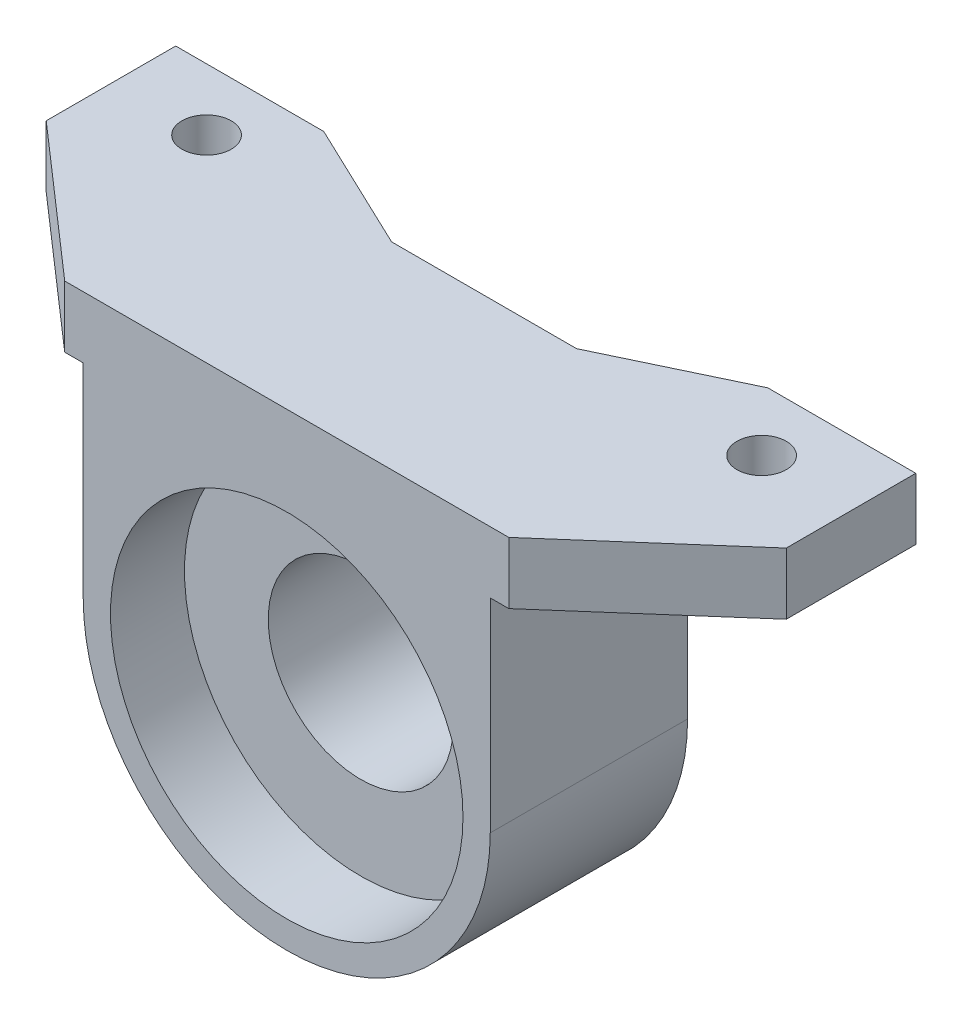
SolidWorks part; units mm, degrees
ref_plane "Plan de face" through (0, 0, 0) normal (0, 0, 1) x (1, 0, 0)
ref_plane "Plan de dessus" through (0, 0, 0) normal (0, 1, 0) x (1, 0, 0)
ref_plane "Plan de droite" through (0, 0, 0) normal (1, 0, 0) x (0, 0, -1)
sketch "Esquisse1" plane through (0, 0, 0) normal (0, 0, 1) x (1, 0, 0)
  circle A0 centre (0, 0) radius 14.29
  circle A1 centre (0, 0) radius 16.5
  dimension "D1" = 28.58
  dimension "D2" = 33
extrude "Boss.-Extru.1" add sketch "Esquisse1" along normal blind 6
sketch "Esquisse2" plane through (0, 0, 0) normal (0, 0, -1) x (-1, 0, 0)
  circle A0 centre (0, 0) radius 16.5
extrude "Boss.-Extru.2" add sketch "Esquisse2" along normal blind 10
ref_plane "Plan2" through (0, 16.5, 0) normal (0, 1, 0) x (1, 0, 0)
sketch "Esquisse3" plane through (0, 16.5, 0) normal (0, 1, 0) x (1, 0, 0)
  line L0 (16.5, 10) -> (-16.5, 10) construction
  line L1 (0, 10) -> (40, 10)
  line L3 (0, -10) -> (40, -10)
  line L4 (40, 10) -> (40, -10)
  line L6 (0, 10) -> (-40, 10)
  line L8 (0, -10) -> (-40, -10)
  line L9 (-40, 10) -> (-40, -10)
  dimension "D1" = 40
  dimension "D2" = 40
  dimension "D3" = 20
extrude "Boss.-Extru.3" add sketch "Esquisse3" along normal blind 5 separate body
ref_plane "Plan3" through (0, 0, -10) normal (0, 0, 1) x (1, 0, 0)
sketch "Esquisse4" plane through (0, 0, -10) normal (0, 0, 1) x (1, 0, 0)
  line L0 (16.5, 16.5) -> (16.5, 0)
  line L1 (8.8, 16.5) -> (-8.8, 16.5) construction
  line L2 (-16.5, 16.5) -> (-16.5, 0)
  line L3 (40, 16.5) -> (-40, 16.5) construction
  line L4 (16.5, 16.5) -> (0, 16.5)
  line L5 (0, 16.5) -> (-16.5, 16.5)
  arc A0 (16.5, 0) -> (0, 16.5) centre (0, 0) ccw
  arc A1 (-16.5, 0) -> (0, 16.5) centre (0, 0) ccw
  circle A2 centre (0, 0) radius 16.5
  dimension "D1" = 16.5
  dimension "D2" = 16.5
  dimension "D3" = 16.5
  dimension "D4" = 16.5
extrude "Boss.-Extru.4" add sketch "Esquisse4" along normal blind 16 contours A2 L5 L2 | A0 L0 L4
sketch "Esquisse7" plane through (0, 21.5, 0) normal (0, 1, 0) x (1, 0, 0)
  line L0 (-40, -10) -> (40, -10) construction
  line L1 (15, -10) -> (-15, -10)
  line L2 (15, -10) -> (15, 10)
  line L3 (15, 10) -> (-15, 10)
  line L4 (-15, -10) -> (-15, 10)
  line L5 (-18.15, 10) -> (18.15, 10) construction
  line L7 (-40, 10) -> (-15, 10)
  line L8 (40, -10) -> (15, -10)
  line L9 (40, -10) -> (40, 10)
  line L10 (40, 10) -> (15, 10)
  line L11 (15, -10) -> (15, 10)
  line L12 (-40, 10) -> (-40, 15)
  line L13 (-40, 15) -> (-15, 15)
  line L14 (-15, 10) -> (-40, 10)
  line L15 (-15, 10) -> (-15, -10)
  line L16 (-15, -10) -> (-40, -10)
  line L17 (-40, 10) -> (-40, -10)
  line L18 (40, -10) -> (30, -10)
  line L19 (40, -10) -> (40, 10)
  line L20 (40, 10) -> (30, 10)
  line L21 (30, -10) -> (30, 10)
  line L22 (-40, -10) -> (-30, -10)
  line L23 (-40, -10) -> (-40, 10)
  line L24 (-40, 10) -> (-30, 10)
  line L25 (-30, -10) -> (-30, 10)
  line L26 (-30, -10) -> (30, -10)
  line L27 (-30, -10) -> (-30, -6)
  line L28 (-30, -6) -> (30, -6)
  line L29 (30, -10) -> (30, -6)
  line L30 (-15, 10) -> (-15, 15)
  line L31 (-30, 10) -> (-15, 10)
  line L32 (-30, 10) -> (-30, 15)
  line L33 (-30, 15) -> (-15, 15)
  line L34 (-15, 10) -> (-15, 15)
  line L35 (15, 10) -> (30, 10)
  line L36 (15, 10) -> (15, 15)
  line L37 (15, 15) -> (30, 15)
  line L38 (30, 10) -> (30, 15)
  circle A0 centre (-22.5, 10) radius 2
  circle A1 centre (22.5, 10) radius 2
  line M10 (40, 10) -> (-40, 10)
  line M11 (-40, 10) -> (-40, -10)
  line M12 (-40, -10) -> (40, -10)
  line M13 (40, -10) -> (40, 10)
  dimension "D1" = 4
  dimension "D2" = 4
  dimension "D3" = 15
  dimension "D4" = 30
  dimension "D5" = 10
  dimension "D6" = 10
  dimension "D7" = 7.5
  dimension "D8" = 7.5
  dimension "D9" = 4
  dimension "D10" = 20
  dimension "D11" = 20
  dimension "D12" = 5
  dimension "D13" = 5
extrude "Enlèv. mat.-Extru.1" cut sketch "Esquisse7" against normal through all contours L25 L14 M12 M11 | L21 L8 M13 M10 | A1 | A0 | L27 L26 L29 L28
sketch "Esquisse8" plane through (0, 0, 0) normal (0, 0, 1) x (1, 0, 0)
  circle A0 centre (0, 0) radius 7.5
extrude "Enlèv. mat.-Extru.2" cut sketch "Esquisse8" against normal through all
sketch "Esquisse10" plane through (0, 0, -10) normal (0, 0, -1) x (-1, 0, 0)
  line L1 (-30, 21.5) -> (30, 21.5)
  line L2 (-30, 21.5) -> (-30, 16.5)
  line L3 (-30, 16.5) -> (30, 16.5)
  line L4 (30, 21.5) -> (30, 16.5)
extrude "Boss.-Extru.5" add sketch "Esquisse10" along normal blind 5
sketch "Esquisse11" plane through (0, 21.5, 0) normal (0, 1, 0) x (1, 0, 0)
  line L0 (-30, 4.5) -> (-18, -6)
  line L1 (-30, -6) -> (-30, 15) construction
  line L2 (-18, -6) -> (18, -6)
  line L3 (-30, -6) -> (30, -6) construction
  line L4 (18, -6) -> (30, 4.5)
  line L5 (30, -6) -> (30, 15) construction
  line L6 (-30, 15) -> (30, 15) construction
  line L7 (18, -6) -> (30, -6)
  line L8 (18, -6) -> (18, 4.5)
  line L9 (18, 4.5) -> (30, 4.5)
  line L10 (30, -6) -> (30, 4.5)
  line L11 (-18, -6) -> (-30, -6)
  line L12 (-18, -6) -> (-18, 4.5)
  line L13 (-18, 4.5) -> (-30, 4.5)
  line L14 (-30, -6) -> (-30, 4.5)
  line L15 (-18, 4.5) -> (-7.5, 4.5)
  line L16 (-18, 4.5) -> (-18, 15)
  line L17 (-18, 15) -> (-7.5, 15)
  line L18 (-7.5, 4.5) -> (-7.5, 15)
  line L19 (-18, 15) -> (-7.5, 10)
  line L20 (18, 4.5) -> (7.5, 4.5)
  line L21 (18, 4.5) -> (18, 15)
  line L22 (18, 15) -> (7.5, 15)
  line L23 (7.5, 4.5) -> (7.5, 15)
  line L24 (-7.5, 15) -> (7.5, 15)
  line L25 (-7.5, 15) -> (-7.5, 10)
  line L26 (-7.5, 10) -> (7.5, 10)
  line L27 (7.5, 15) -> (7.5, 10)
  line L28 (7.5, 10) -> (18, 15)
  line L29 (-18, 15) -> (-7.5, 15)
  line L30 (-7.5, 10) -> (7.5, 10)
  line L31 (7.5, 15) -> (18, 15)
  circle A0 centre (-22.5, 10) radius 2
  circle A1 centre (22.5, 10) radius 2
  line M3 (20.5, 10) -> (24.5, 10)
  line M5 (-24.5, 10) -> (-20.5, 10)
  line M7 (30, -6) -> (30, 15)
  line M8 (30, 15) -> (-30, 15)
  line M9 (-30, 15) -> (-30, -6)
  line M10 (-30, -6) -> (30, -6)
  dimension "D1" = 12
  dimension "D2" = 12
  dimension "D3" = 10.5
  dimension "D4" = 10.5
extrude "Enlèv. mat.-Extru.4" cut sketch "Esquisse11" against normal blind 5 contours L0 M9 M10 | L4 M10 M7 | A1 M3 | A0 M5 | L19 L18 M8 | L18 L26 L23 M8 | L23 L28 M8
